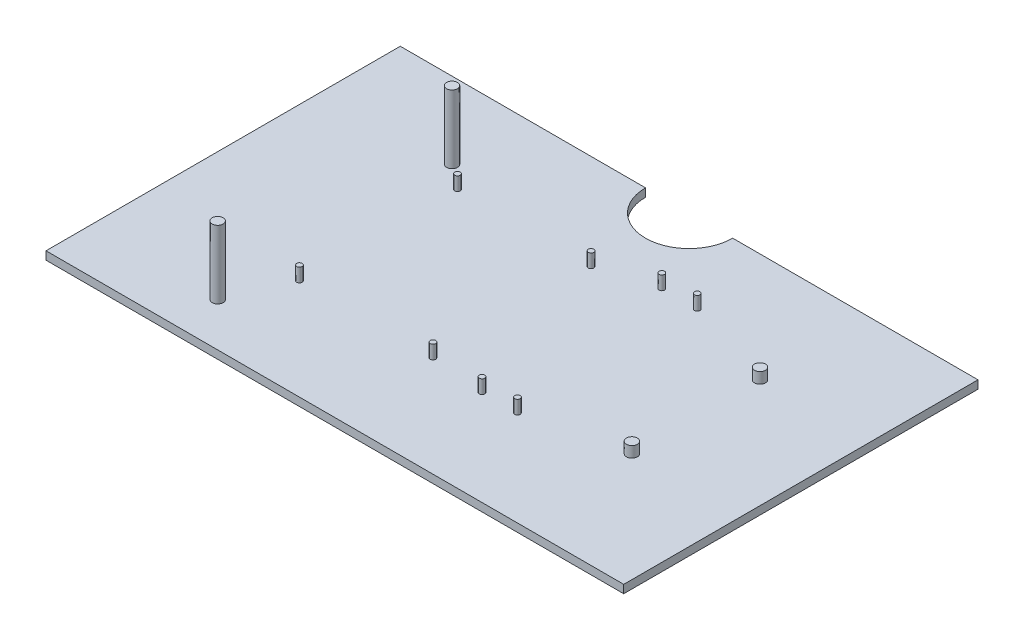
SolidWorks part; units mm, degrees
ref_plane "Front Plane" through (0, 0, 0) normal (0, 0, 1) x (1, 0, 0)
ref_plane "Top Plane" through (0, 0, 0) normal (0, 1, 0) x (1, 0, 0)
ref_plane "Right Plane" through (0, 0, 0) normal (1, 0, 0) x (0, 0, -1)
sketch "Sketch3" plane through (0, 0, 0) normal (0, 1, 0) x (1, 0, 0)
  line L0 (-106, 65) -> (-106, -65)
  line L1 (-106, -65) -> (106, -65)
  line L2 (106, -65) -> (106, 65)
  line L3 (106, 65) -> (-106, 65)
  point P2 (0, 65)
  point P5 (-106, 0)
  dimension "D1" = 212
  dimension "D2" = 130
extrude "Boss-Extrude1" add sketch "Sketch3" along normal blind 3
sketch "Sketch4" plane through (0, 3, 0) normal (0, 1, 0) x (1, 0, 0)
  line L0 (106, -65) -> (106, 65) construction
  line L1 (106, 65) -> (-106, 65) construction
  circle A0 centre (66, 25) radius 2
  circle A1 centre (66, -22) radius 2
  dimension "D1" = 4
  dimension "D2" = 4
  dimension "D3" = 47
  dimension "D4" = 40
  dimension "D5" = 40
extrude "Boss-Extrude2" add sketch "Sketch4" along normal blind 4
sketch "Sketch5" plane through (0, 3, 0) normal (0, 1, 0) x (1, 0, 0)
  line L0 (-106, 65) -> (-106, -65) construction
  line L1 (-106, -65) -> (106, -65) construction
  circle A0 centre (-50, 30) radius 1
  circle A1 centre (-1, 30) radius 1
  circle A2 centre (-1, -28) radius 1
  circle A3 centre (-50, -28) radius 1
  dimension "D1" = 2
  dimension "D2" = 2
  dimension "D3" = 2
  dimension "D4" = 2
  dimension "D5" = 49
  dimension "D6" = 58
  dimension "D7" = 105
  dimension "D8" = 37
extrude "Boss-Extrude3" add sketch "Sketch5" along normal blind 5
sketch "Sketch6" plane through (0, 3, 0) normal (0, 1, 0) x (1, 0, 0)
  circle A0 centre (-59, -49) radius 2
  circle A1 centre (-59, 37) radius 2
  circle A2 centre (-50, -28) radius 1 construction
  dimension "D1" = 21
  dimension "D2" = 4
  dimension "D3" = 4
  dimension "D4" = 9
  dimension "D5" = 86
extrude "Boss-Extrude4" add sketch "Sketch6" along normal blind 25
sketch "Sketch7" plane through (0, 3, 0) normal (0, 1, 0) x (1, 0, 0)
  line L0 (-106, -65) -> (106, -65) construction
  circle A0 centre (19, 36) radius 1
  circle A1 centre (32, 36) radius 1
  circle A2 centre (32, -30) radius 1
  circle A3 centre (19, -30) radius 1
  circle A4 centre (-1, -28) radius 1 construction
  dimension "D1" = 2
  dimension "D2" = 2
  dimension "D3" = 2
  dimension "D4" = 2
  dimension "D5" = 13
  dimension "D6" = 66
  dimension "D7" = 35
  dimension "D8" = 20
extrude "Boss-Extrude5" add sketch "Sketch7" along normal blind 5
sketch "Sketch8" plane through (0, 3, 0) normal (0, 1, 0) x (1, 0, 0)
  line L0 (106, 65) -> (-106, 65) construction
  circle A0 centre (0, 65) radius 16
  dimension "D1" = 32
extrude "Cut-Extrude1" cut sketch "Sketch8" against normal blind 10
